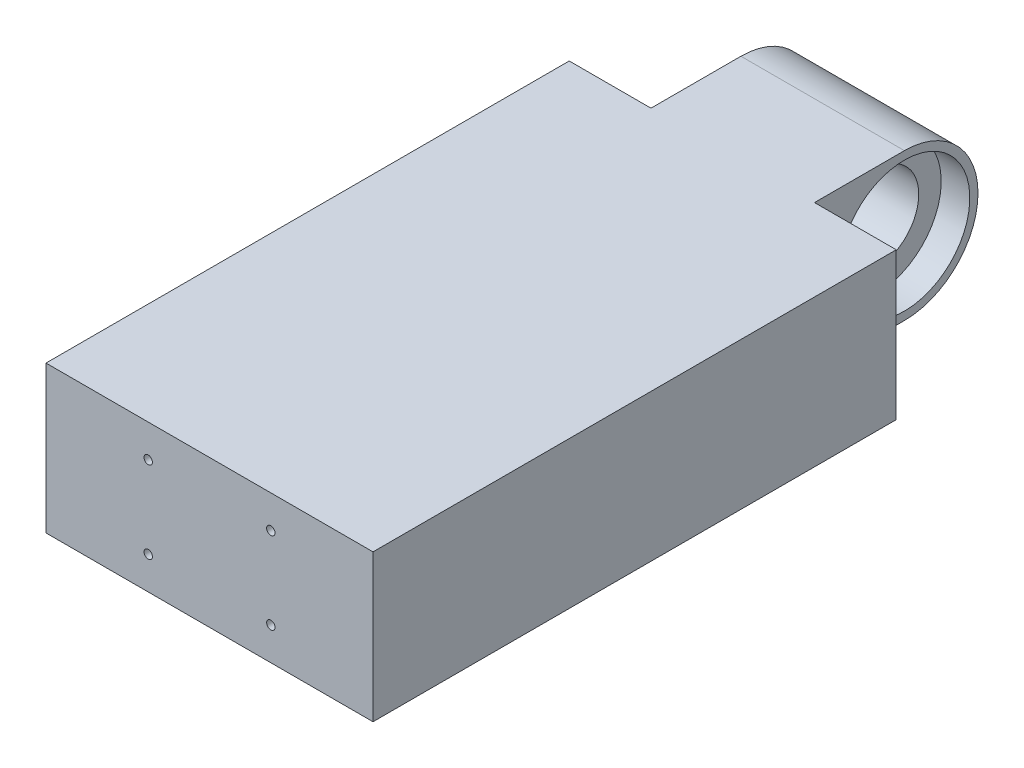
SolidWorks part; units mm, degrees
ref_plane "정면" through (0, 0, 0) normal (0, 0, 1) x (1, 0, 0)
ref_plane "윗면" through (0, 0, 0) normal (0, 1, 0) x (1, 0, 0)
ref_plane "우측면" through (0, 0, 0) normal (1, 0, 0) x (0, 0, -1)
sketch "Sketch1" plane through (0, 0, 0) normal (0, 0, 1) x (1, 0, 0)
  line L5 (0, 0) -> (80, 0)
  line L6 (0, 0) -> (0, 36)
  line L7 (0, 36) -> (80, 36)
  line L8 (80, 0) -> (80, 36)
  dimension "D1" = 36
  dimension "D2" = 80
extrude "Boss-Extrude1" add sketch "Sketch1" along normal blind 150
sketch "Sketch2" plane through (0, 0, 150) normal (0, 0, 1) x (1, 0, 0)
  line L0 (40, 36) -> (40, 0) construction
  line L1 (80, 36) -> (0, 36) construction
  line L2 (0, 0) -> (80, 0) construction
  line L3 (40, 18) -> (66.7896, 18) construction
  point P8 (55, 28)
  point P9 (55, 8)
  point P10 (25, 8)
  point P11 (25, 28)
  dimension "D1" = 20
  dimension "D2" = 10
  dimension "D3" = 30
hole_wizard "M2.5 Tapped Hole1" positions "3DSketch1" profile "Sketch3" tap size "M2.5" standard "KS"
sketch3d "3DSketch1"
  point P0 (25, 28, 150)
  point P3 (55, 28, 150)
  point P6 (55, 8, 150)
  point P9 (25, 8, 150)
sketch "Sketch3" plane through (25, 28, 150) normal (1, 0, 0) x (0, -1, 0)
  line L0 (0, 0) -> (0, 3.9659)
  line L1 (0, 3.9659) -> (1.025, 3.35)
  line L2 (1.025, 3.35) -> (1.025, 0)
  line L5 (1.025, 0) -> (0, 0)
  line L10 (0, 3.9659) -> (-1.025, 3.35) construction
  line L11 (0, -6.35) -> (0, 107.95) construction
  dimension "Tap Drill Dia." = 2.05
  dimension "Tap Drill Depth" = 3.35
  dimension "Drill Angle" = 118
cosmetic thread "Hole Thread1" parameters "D1"=2, "D2"=2.5
cosmetic thread "Hole Thread2" parameters "D1"=2, "D2"=2.5
cosmetic thread "Hole Thread3" parameters "D1"=2, "D2"=2.5
cosmetic thread "Hole Thread4" parameters "D1"=2, "D2"=2.5
sketch "Sketch4" plane through (0, 0, 0) normal (-1, 0, 0) x (0, 0, 1)
  line L0 (0, 36) -> (0, 0) construction
  line L1 (0, 36) -> (0, 0)
  arc A0 (0, 36) -> (0, 0) centre (0, 18) ccw
extrude "Boss-Extrude2" add sketch "Sketch4" against normal blind 80
sketch "Sketch5" plane through (0, 0, 0) normal (-1, 0, 0) x (0, 0, 1)
  circle A1 centre (0, 18) radius 10.5
  dimension "D1" = 21
sketch "Sketch7" plane through (0, 36, 0) normal (0, 1, 0) x (1, 0, 0)
  line L0 (40, 0) -> (40, 35.2048) construction
  line L1 (80, 0) -> (0, 0) construction
  line L2 (20, 18) -> (20, -22)
  line L3 (80, 18) -> (60, 18)
  line L4 (80, 18) -> (80, -22)
  line L5 (80, -22) -> (60, -22)
  line L6 (60, 18) -> (60, -22)
  line L7 (0, -22) -> (20, -22)
  line L8 (0, 18) -> (0, -22)
  line L9 (0, 18) -> (20, 18)
  dimension "D1" = 40
  dimension "D2" = 20
extrude "Cut-Extrude4" cut sketch "Sketch7" against normal blind 80
extrude "Cut-Extrude5" cut sketch "Sketch5" against normal blind 80
sketch "Sketch8" plane through (20, 0, 0) normal (-1, 0, 0) x (0, 0, 1)
  circle A0 centre (0, 18) radius 16
extrude "Cut-Extrude6" cut sketch "Sketch8" against normal blind 7
ref_plane "Plane1" through (40, 0, 0) normal (-1, 0, 0) x (0, 0, 1)
mirror "Mirror1" about plane through (40, 0, 0) normal (-1, 0, 0) of "Cut-Extrude6"
